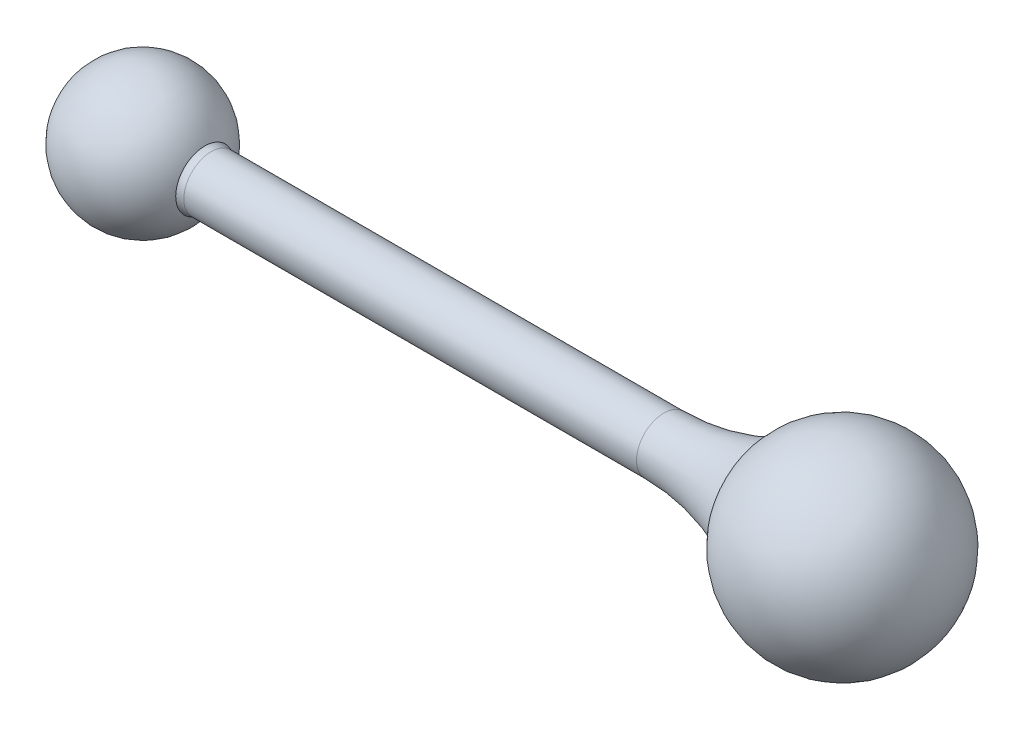
SolidWorks part; units mm, degrees
ref_plane "Ön Düzlem" through (0, 0, 0) normal (0, 0, 1) x (1, 0, 0)
ref_plane "Üst Düzlem" through (0, 0, 0) normal (0, 1, 0) x (1, 0, 0)
ref_plane "Sağ Düzlem" through (0, 0, 0) normal (1, 0, 0) x (0, 0, -1)
sketch "Sketch1" plane through (0, 0, 0) normal (0, 0, 1) x (1, 0, 0)
  line L0 (0, 0) -> (-19.798, 0) construction
  line L1 (0, 0) -> (-14, 0)
  arc A0 (-14, 0) -> (0, 0) centre (-7, 0) ccw
  dimension "D1" = 14
revolve "Revolve1" add sketch "Sketch1" angle 360 about L0
sketch "Sketch2" plane through (0, 0, 0) normal (0, 0, 1) x (1, 0, 0)
  line L0 (0, 0) -> (-48.3923, 0) construction
  line L1 (-14, 0) -> (-63, 0)
  line L2 (-53, -2) -> (-20, -2)
  line L4 (-24.1962, 0) -> (-14, 0)
  arc A0 (-63, 0) -> (-53.4706, -2.1176) centre (-58, 0) ccw
  arc A1 (-53.4706, -2.1176) -> (-53, -2) centre (-53, -3) cw
  arc A2 (-20, -2) -> (-13.0775, -3.4733) centre (-20, -19) cw
  circle A3 centre (-7, 0) radius 7 construction
  arc A4 (-14, 0) -> (-13.0775, -3.4733) centre (-7, 0) ccw
  dimension "D3" = 5
  dimension "D4" = 1
  dimension "D5" = 17
  dimension "D6" = 53
  dimension "D1" = 49
  dimension "D2" = 2
  dimension "D7" = 20
revolve "Revolve2" add sketch "Sketch2" angle 360 about L0
